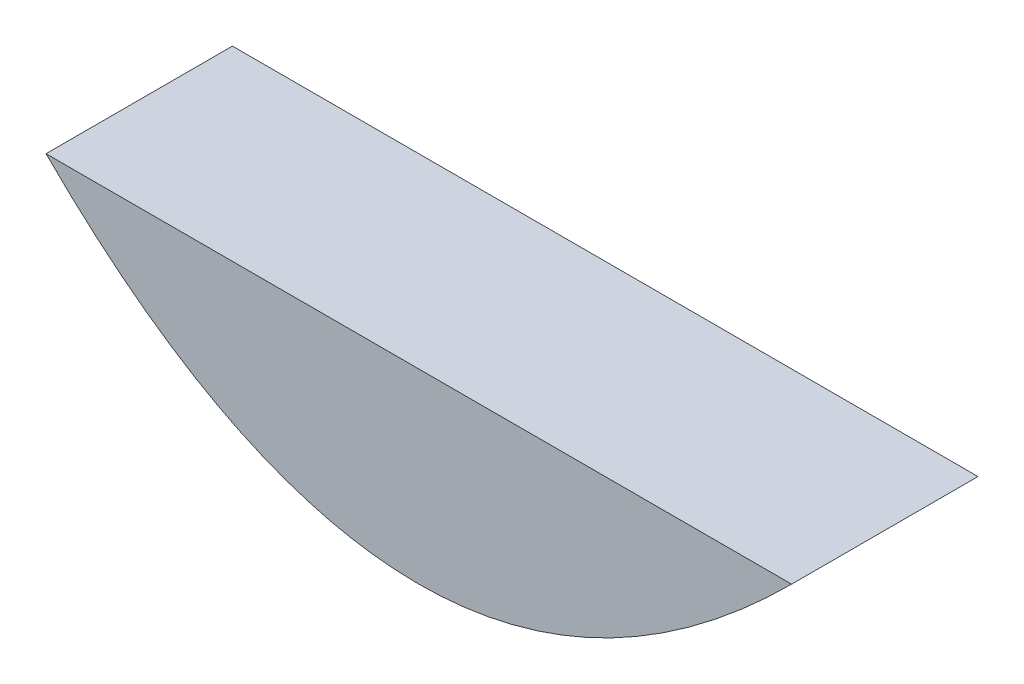
SolidWorks part; units mm, degrees
ref_plane "Front Plane" through (0, 0, 0) normal (0, 0, 1) x (1, 0, 0)
ref_plane "Top Plane" through (0, 0, 0) normal (0, 1, 0) x (1, 0, 0)
ref_plane "Right Plane" through (0, 0, 0) normal (1, 0, 0) x (0, 0, -1)
sketch "Sketch1" plane through (0, 0, 0) normal (0, 0, 1) x (1, 0, 0)
  line L0 (5, 10) -> (25, 10)
  parabola Q0 (5, 10) -> (25, 10) focus (15, 10) apex (15, 5)
  dimension "D1" = 15
  dimension "D2" = 10
  dimension "D3" = 5
  dimension "D4" = 15
  dimension "D5" = 20
extrude "Boss-Extrude1" add sketch "Sketch1" along normal blind 5
